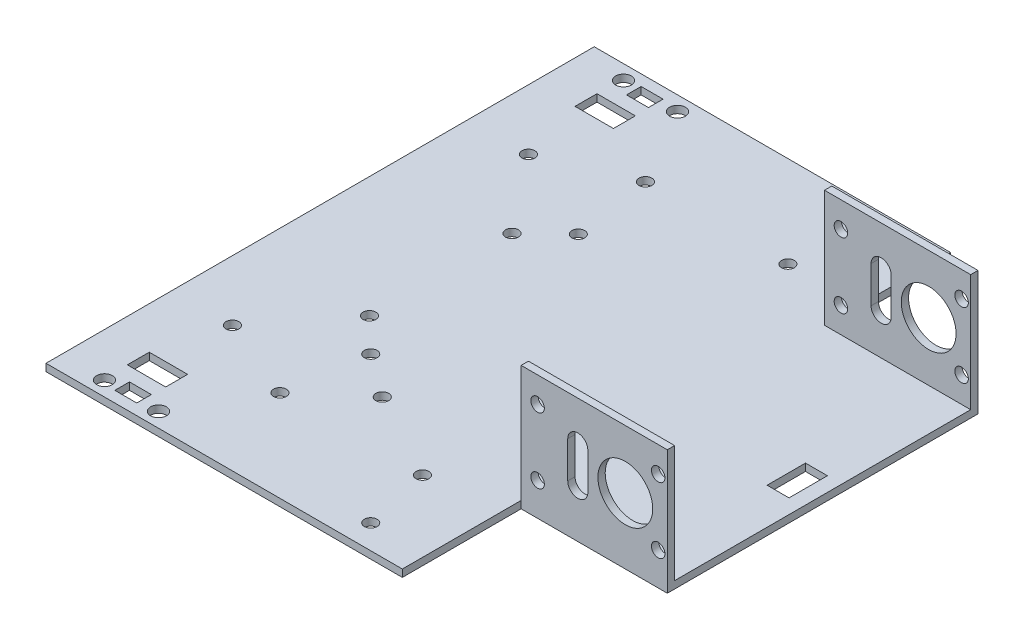
SolidWorks part; units mm, degrees
ref_plane "Front" through (0, 0, 0) normal (0, 0, 1) x (1, 0, 0)
ref_plane "Top" through (0, 0, 0) normal (0, 1, 0) x (1, 0, 0)
ref_plane "Right" through (0, 0, 0) normal (1, 0, 0) x (0, 0, -1)
sketch "Sketch1" plane through (0, 0, 0) normal (0, 1, 0) x (1, 0, 0)
  line L0 (-68.75, -75) -> (33.25, -75)
  line L1 (33.25, -75) -> (33.25, -42.5)
  line L2 (33.25, -42.5) -> (68.75, -42.5)
  line L3 (68.75, -42.5) -> (68.75, 42.5)
  line L4 (68.75, 42.5) -> (33.25, 42.5)
  line L5 (33.25, 42.5) -> (33.25, 75)
  line L6 (33.25, 75) -> (-68.75, 75)
  line L7 (-68.75, 75) -> (-68.75, -75)
  line L8 (-57.25, -64.25) -> (-57.25, -58.25)
  line L9 (-57.25, -58.25) -> (-46.75, -58.25)
  line L10 (-46.75, -58.25) -> (-46.75, -64.25)
  line L11 (-46.75, -64.25) -> (-57.25, -64.25)
  line L12 (-52.92, -68) -> (-46.92, -68)
  line L13 (-46.92, -68) -> (-46.92, -72)
  line L14 (-46.92, -72) -> (-52.92, -72)
  line L15 (-52.92, -72) -> (-52.92, -68)
  line L16 (-57.25, 64.25) -> (-46.75, 64.25)
  line L17 (-46.75, 64.25) -> (-46.75, 58.25)
  line L18 (-46.75, 58.25) -> (-57.25, 58.25)
  line L19 (-57.25, 58.25) -> (-57.25, 64.25)
  line L20 (-52.92, 68) -> (-46.92, 68)
  line L21 (-46.92, 68) -> (-46.92, 72)
  line L22 (-46.92, 72) -> (-52.92, 72)
  line L23 (-52.92, 72) -> (-52.92, 68)
  line L24 (58.7962, -5.25) -> (64.7962, -5.25)
  line L25 (64.7962, -5.25) -> (64.7962, 5.25)
  line L26 (64.7962, 5.25) -> (58.7962, 5.25)
  line L27 (58.7962, 5.25) -> (58.7962, -5.25)
  circle A0 centre (-56.75, -71) radius 2.15
  circle A1 centre (-41.97, -71) radius 2.15
  circle A2 centre (-52.25, -40.5) radius 1.75
  circle A3 centre (-29.75, -50) radius 1.75
  circle A4 centre (-35.75, -19.5) radius 1.75
  circle A5 centre (-26.5, -28.4) radius 1.75
  circle A6 centre (-14.75, -37) radius 1.75
  circle A7 centre (9.25, -50) radius 1.75
  circle A8 centre (13.5, -68.4) radius 1.75
  circle A10 centre (-52.25, 40.5) radius 1.75
  circle A11 centre (-35.75, 19.5) radius 1.75
  circle A12 centre (-56.75, 71) radius 2.15
  circle A13 centre (-41.97, 71) radius 2.15
  circle A14 centre (-29.75, 50) radius 1.75
  circle A15 centre (-26.5, 28.4) radius 1.75
  circle A16 centre (9.25, 50) radius 1.75
  circle A17 centre (13.5, 68.4) radius 1.75
  point P66 (-46.92, 70)
  point P67 (-49.92, 72)
  point P68 (-57.25, 61.25)
  point P69 (-52, 64.25)
  point P70 (-49.92, -72)
  point P71 (-52.92, -70)
  dimension "D1" = 4.3
  dimension "D2" = 3.5
  dimension "D13" = 6.6
  dimension "D14" = 82.25
  dimension "D15" = 16.5
  dimension "D17" = 25
  dimension "D18" = 78
  dimension "D19" = 16.5
  dimension "D20" = 34.5
  dimension "D21" = 4
  dimension "D22" = 12
  dimension "D23" = 6
  dimension "D24" = 26.78
  dimension "D32" = 25
  dimension "D33" = 39
  dimension "D34" = 42.25
  dimension "D35" = 46.6
  dimension "D36" = 55.5
  dimension "D37" = 33
  dimension "D4" = 12
  dimension "D5" = 4
  dimension "D6" = 4
  dimension "D38" = 26.78
  dimension "D47" = 33
  dimension "D48" = 55.5
  dimension "D49" = 46.6
  dimension "D50" = 42.25
  dimension "D51" = 39
  dimension "D52" = 25
  dimension "D53" = 38
  dimension "D54" = 54
  dimension "D55" = 6.6
  dimension "D56" = 82.25
  dimension "D57" = 78
  dimension "D58" = 25
  dimension "D16" = 4
  dimension "D7" = 85
  dimension "D8" = 150
  dimension "D9" = 102
  dimension "D10" = 35.5
  dimension "D11" = 32.5
  dimension "D12" = 35.5
  dimension "D25" = 4
  dimension "D26" = 5
  dimension "D27" = 18.83
  dimension "D28" = 10.5
  dimension "D29" = 6
  dimension "D30" = 13.75
  dimension "D31" = 16.75
  dimension "D39" = 18.83
  dimension "D40" = 6
  dimension "D41" = 4
  dimension "D42" = 5
  dimension "D43" = 11.5
  dimension "D44" = 16.75
  dimension "D45" = 10.5
  dimension "D46" = 6
  dimension "D61" = 10.5
  dimension "D62" = 6
  dimension "D63" = 3.9538
  dimension "D64" = 37.25
extrude "Boss-Extrude1" add sketch "Sketch1" along normal blind 2
sketch "Sketch2" plane through (0, 0, 0) normal (0, -1, 0) x (-1, 0, 0)
  line L0 (-68.75, 42.5) -> (-68.75, 40.5)
  line L1 (-68.75, -42.5) -> (-68.75, 42.5) construction
  line L2 (-68.75, 40.5) -> (-28.75, 40.5)
  line L3 (-28.75, 40.5) -> (-28.75, 42.5)
  line L4 (-28.75, 42.5) -> (-68.75, 42.5)
  line L5 (-68.75, 0) -> (0, 0) construction
  line L6 (-28.75, -42.5) -> (-68.75, -42.5)
  line L7 (-28.75, -40.5) -> (-28.75, -42.5)
  line L8 (-68.75, -40.5) -> (-28.75, -40.5)
  line L9 (-68.75, -42.5) -> (-68.75, -40.5)
  dimension "D1" = 2
  dimension "D2" = 40
extrude "Boss-Extrude2" add sketch "Sketch2" against normal blind 34
sketch "Sketch4" plane through (0, 0, -42.5) normal (0, 0, -1) x (-1, 0, 0)
  line L0 (-47, 13) -> (-47, 23)
  line L2 (-41.5, 23) -> (-41.5, 13)
  circle A0 centre (-66.25, 27) radius 1.85
  circle A1 centre (-33.25, 27) radius 1.85
  circle A2 centre (-33.25, 9) radius 1.85
  circle A3 centre (-66.25, 9) radius 1.85
  circle A4 centre (-57.25, 18) radius 7.5
  arc A7 (-41.5, 23) -> (-47, 23) centre (-44.25, 23) ccw
  arc A8 (-47, 13) -> (-41.5, 13) centre (-44.25, 13) ccw
  dimension "D1" = 3.7
  dimension "D2" = 15
  dimension "D3" = 5.5
  dimension "D4" = 5.5
  dimension "D5" = 10
extrude "Cut-Extrude2" cut sketch "Sketch4" against normal blind 120
sketch "Sketch5" plane through (0, 2, 0) normal (0, 1, 0) x (1, 0, 0)
  line L0 (28.75, -42.5) -> (28.75, -75)
  line L1 (-68.75, -75) -> (33.25, -75) construction
  line L2 (28.75, -75) -> (33.25, -75)
  line L3 (33.25, -75) -> (33.25, -42.5)
  line L4 (33.25, -42.5) -> (28.75, -42.5)
  line L5 (68.75, 0) -> (0, 0) construction
  line L6 (68.75, -40.5) -> (68.75, 40.5) construction
  line L7 (33.25, 42.5) -> (28.75, 42.5)
  line L8 (33.25, 75) -> (33.25, 42.5)
  line L9 (28.75, 75) -> (33.25, 75)
  line L10 (28.75, 42.5) -> (28.75, 75)
extrude "Cut-Extrude3" cut sketch "Sketch5" against normal blind 120 contours L7 L10 L9 L8 | L4 L0 L2 L3
